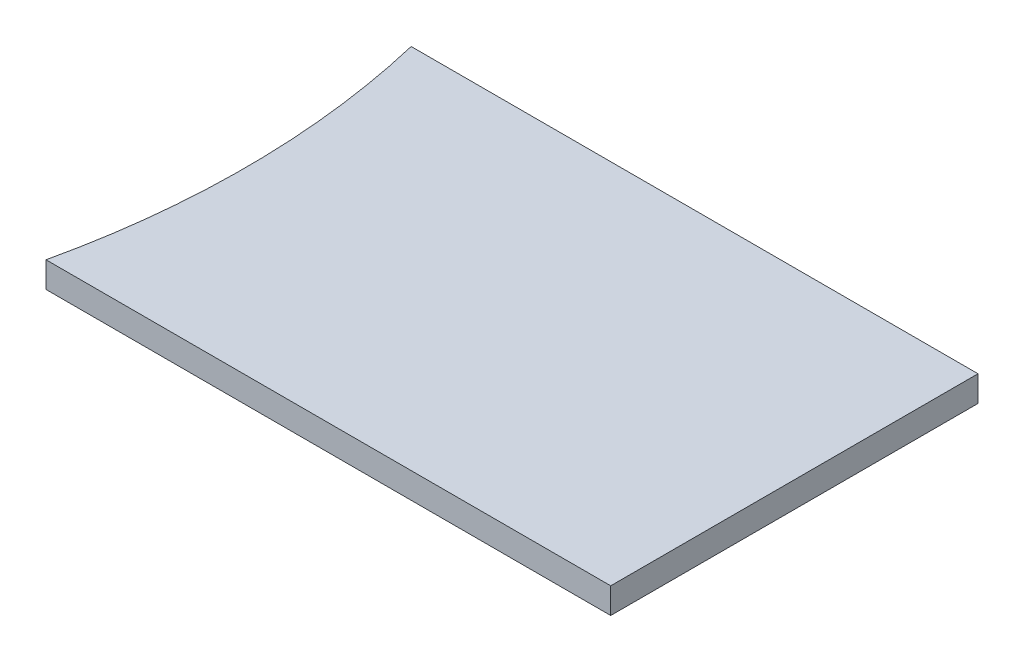
SolidWorks part; units mm, degrees
ref_plane "Front" through (0, 0, 0) normal (0, 0, 1) x (1, 0, 0)
ref_plane "Top" through (0, 0, 0) normal (0, 1, 0) x (1, 0, 0)
ref_plane "Right" through (0, 0, 0) normal (1, 0, 0) x (0, 0, -1)
sketch "Sketch1" plane through (0, 0, 0) normal (0, 1, 0) x (1, 0, 0)
  line L1 (0, 0) -> (34.5004, 0)
  line L2 (0, 0) -> (0, 21.4)
  line L3 (0, 21.4) -> (34.5004, 21.4)
  line L4 (34.5004, 0) -> (34.5004, 21.4)
  dimension "D1" = 21.4
extrude "Boss-Extrude1" add sketch "Sketch1" along normal blind 1.5
sketch "Sketch2" plane through (0, 1.5, 0) normal (0, 1, 0) x (1, 0, 0)
  line L0 (20.4624, 10.434) -> (-44.5376, 10.434)
  circle A0 centre (-44.5376, 10.434) radius 47.3
  dimension "D1" = 65
extrude "Cut-Extrude1" cut sketch "Sketch2" against normal blind 1.5
